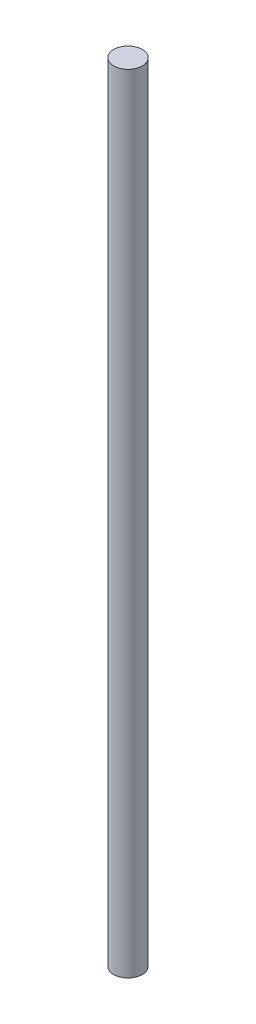
SolidWorks part; units mm, degrees
material "AISI 1020"
ref_plane "Plano frontal" through (0, 0, 0) normal (0, 0, 1) x (1, 0, 0)
ref_plane "Plano superior" through (0, 0, 0) normal (0, 1, 0) x (1, 0, 0)
ref_plane "Plano direito" through (0, 0, 0) normal (1, 0, 0) x (0, 0, -1)
sketch "Esboço1" plane through (0, 0, 0) normal (0, 1, 0) x (1, 0, 0)
  circle A0 centre (0, 0) radius 4
  dimension "D1" = 8
extrude "Ressalto-extrusão1" add sketch "Esboço1" along normal blind 220
